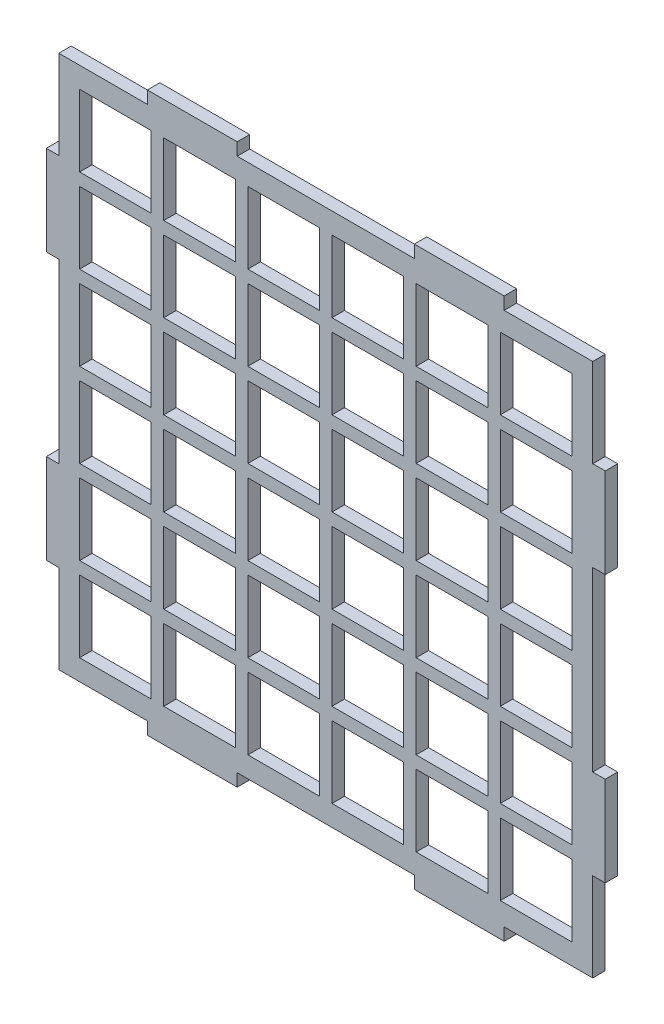
SolidWorks part; units mm, degrees
ref_plane "Front Plane" through (0, 0, 0) normal (0, 0, 1) x (1, 0, 0)
ref_plane "Top Plane" through (0, 0, 0) normal (0, 1, 0) x (1, 0, 0)
ref_plane "Right Plane" through (0, 0, 0) normal (1, 0, 0) x (0, 0, -1)
sketch "Sketch1" plane through (0, 0, 0) normal (0, 0, 1) x (1, 0, 0)
  line L0 (-64.15, -64.15) -> (64.15, 64.15) construction
  line L1 (42.5667, -64.15) -> (42.8667, -64.15)
  line L2 (21.2833, -64.15) -> (42.5667, -64.15) construction
  line L3 (0, -64.15) -> (-21.2833, -64.15)
  line L4 (21.2833, -64.15) -> (0, -64.15)
  line L5 (-42.8667, -64.15) -> (-64.15, -64.15)
  line L6 (64.15, 0) -> (64.15, 21.2833)
  line L7 (64.15, -21.2833) -> (64.15, 0)
  line L8 (64.15, -42.8667) -> (64.15, -64.15)
  line L9 (64.15, -64.15) -> (42.8667, -64.15)
  line L10 (64.15, 64.15) -> (64.15, 42.8667)
  line L11 (-21.2833, -64.15) -> (-21.2833, -67.15)
  line L12 (-42.8667, -67.15) -> (-42.8667, -64.15)
  line L13 (-21.2833, -67.15) -> (-42.8667, -67.15)
  line L14 (42.8667, -64.15) -> (42.8667, -67.15)
  line L15 (21.2833, -67.15) -> (21.2833, -64.15)
  line L16 (42.8667, -67.15) -> (21.2833, -67.15)
  line L17 (64.15, -21.2833) -> (67.15, -21.2833)
  line L18 (42.8667, 67.15) -> (21.2833, 67.15)
  line L19 (21.2833, 67.15) -> (21.2833, 64.15)
  line L21 (42.8667, 64.15) -> (42.8667, 67.15)
  line L22 (-21.2833, 67.15) -> (-42.8667, 67.15)
  line L23 (-42.8667, 67.15) -> (-42.8667, 64.15)
  line L25 (-21.2833, 64.15) -> (-21.2833, 67.15)
  line L26 (-67.15, 42.8667) -> (-67.15, 21.2833)
  line L27 (-67.15, 21.2833) -> (-64.15, 21.2833)
  line L29 (-64.15, 42.8667) -> (-67.15, 42.8667)
  line L30 (-67.15, -21.2833) -> (-67.15, -42.8667)
  line L31 (-67.15, -42.8667) -> (-64.15, -42.8667)
  line L33 (-64.15, -21.2833) -> (-67.15, -21.2833)
  line L34 (64.15, 64.15) -> (42.8667, 64.15)
  line L35 (-64.15, 64.15) -> (-64.15, 42.8667)
  line L36 (-42.8667, 64.15) -> (-64.15, 64.15)
  line L37 (-21.2833, 64.15) -> (0, 64.15)
  line L38 (0, 64.15) -> (21.2833, 64.15)
  line L39 (-64.15, -42.8667) -> (-64.15, -64.15)
  line L40 (-64.15, 21.2833) -> (-64.15, 0)
  line L41 (-64.15, 0) -> (-64.15, -21.2833)
  line L42 (-64.15, 21.2833) -> (-64.15, 42.5667) construction
  line L43 (-64.15, 42.5667) -> (-64.15, 42.8667) construction
  line L44 (67.15, -42.8667) -> (64.15, -42.8667)
  line L45 (67.15, -21.2833) -> (67.15, -42.8667)
  line L46 (64.15, 42.8667) -> (67.15, 42.8667)
  line L47 (67.15, 21.2833) -> (64.15, 21.2833)
  line L48 (67.15, 42.8667) -> (67.15, 21.2833)
  point P7 (0, 0)
  point P10 (0, 0)
  dimension "D1" = 3
  dimension "D2" = 128.3
  dimension "D3" = 0.3
extrude "Boss-Extrude1" add sketch "Sketch1" along normal blind 3 contours L39 L0 L34 L21 L18 L19 L38 L37 L25 L22 L23 L36 L35 L43 L42 L40 L41 L33 L30 L31 | L0 L5 L12 L13 L11 L3 L4 L2 L1 L9 L8 L44 L45 L17 L7 L6 L47 L48 L46 L10
sketch "Sketch2" plane through (0, 0, 3) normal (0, 0, 1) x (1, 0, 0)
  line L0 (-64.15, 59.15) -> (-59.15, 59.15) construction
  line L1 (-64.15, 64.15) -> (-64.15, 42.8667) construction
  line L2 (-59.15, 59.15) -> (-59.15, 64.15) construction
  line L3 (-42.8667, 64.15) -> (-64.15, 64.15) construction
  line L4 (-64.15, -64.15) -> (64.15, 64.15) construction
  line L5 (-64.15, -64.15) -> (64.15, 64.15) construction
  line L6 (59.15, -64.15) -> (59.15, -59.15) construction
  line L7 (59.15, -59.15) -> (64.15, -59.15) construction
  line L8 (-59.15, 59.15) -> (-59.15, 41.9333)
  line L9 (-59.15, 59.15) -> (-41.9333, 59.15)
  line L10 (-59.15, 41.9333) -> (-41.9333, 41.9333)
  line L11 (-41.9333, 59.15) -> (-41.9333, 41.9333)
  line L12 (-38.9333, 59.15) -> (-38.9333, 41.9333)
  line L13 (-38.9333, 59.15) -> (-21.7167, 59.15)
  line L14 (-21.7167, 59.15) -> (-21.7167, 41.9333)
  line L15 (-38.9333, 41.9333) -> (-21.7167, 41.9333)
  line L16 (-18.7167, 59.15) -> (-18.7167, 41.9333)
  line L17 (-18.7167, 59.15) -> (-1.5, 59.15)
  line L18 (-1.5, 59.15) -> (-1.5, 41.9333)
  line L19 (-18.7167, 41.9333) -> (-1.5, 41.9333)
  line L20 (1.5, 59.15) -> (1.5, 41.9333)
  line L21 (1.5, 59.15) -> (18.7167, 59.15)
  line L22 (18.7167, 59.15) -> (18.7167, 41.9333)
  line L23 (1.5, 41.9333) -> (18.7167, 41.9333)
  line L24 (21.7167, 59.15) -> (21.7167, 41.9333)
  line L25 (21.7167, 59.15) -> (38.9333, 59.15)
  line L26 (38.9333, 59.15) -> (38.9333, 41.9333)
  line L27 (21.7167, 41.9333) -> (38.9333, 41.9333)
  line L28 (41.9333, 59.15) -> (41.9333, 41.9333)
  line L29 (41.9333, 59.15) -> (59.15, 59.15)
  line L30 (59.15, 59.15) -> (59.15, 41.9333)
  line L31 (41.9333, 41.9333) -> (59.15, 41.9333)
  line L32 (-38.9333, 38.9333) -> (-38.9333, 21.7167)
  line L33 (-38.9333, 38.9333) -> (-21.7167, 38.9333)
  line L34 (-21.7167, 38.9333) -> (-21.7167, 21.7167)
  line L35 (-38.9333, 21.7167) -> (-21.7167, 21.7167)
  line L36 (-18.7167, 38.9333) -> (-18.7167, 21.7167)
  line L37 (-18.7167, 38.9333) -> (-1.5, 38.9333)
  line L38 (-1.5, 38.9333) -> (-1.5, 21.7167)
  line L39 (-18.7167, 21.7167) -> (-1.5, 21.7167)
  line L40 (1.5, 38.9333) -> (1.5, 21.7167)
  line L41 (1.5, 38.9333) -> (18.7167, 38.9333)
  line L42 (18.7167, 38.9333) -> (18.7167, 21.7167)
  line L43 (1.5, 21.7167) -> (18.7167, 21.7167)
  line L44 (21.7167, 38.9333) -> (21.7167, 21.7167)
  line L45 (21.7167, 38.9333) -> (38.9333, 38.9333)
  line L46 (38.9333, 38.9333) -> (38.9333, 21.7167)
  line L47 (21.7167, 21.7167) -> (38.9333, 21.7167)
  line L48 (41.9333, 38.9333) -> (41.9333, 21.7167)
  line L49 (41.9333, 38.9333) -> (59.15, 38.9333)
  line L50 (59.15, 38.9333) -> (59.15, 21.7167)
  line L51 (41.9333, 21.7167) -> (59.15, 21.7167)
  line L52 (-38.9333, 18.7167) -> (-38.9333, 1.5)
  line L53 (-38.9333, 18.7167) -> (-21.7167, 18.7167)
  line L54 (-21.7167, 18.7167) -> (-21.7167, 1.5)
  line L55 (-38.9333, 1.5) -> (-21.7167, 1.5)
  line L56 (-18.7167, 18.7167) -> (-18.7167, 1.5)
  line L57 (-18.7167, 18.7167) -> (-1.5, 18.7167)
  line L58 (-1.5, 18.7167) -> (-1.5, 1.5)
  line L59 (-18.7167, 1.5) -> (-1.5, 1.5)
  line L60 (1.5, 18.7167) -> (1.5, 1.5)
  line L61 (1.5, 18.7167) -> (18.7167, 18.7167)
  line L62 (18.7167, 18.7167) -> (18.7167, 1.5)
  line L63 (1.5, 1.5) -> (18.7167, 1.5)
  line L64 (21.7167, 18.7167) -> (21.7167, 1.5)
  line L65 (21.7167, 18.7167) -> (38.9333, 18.7167)
  line L66 (38.9333, 18.7167) -> (38.9333, 1.5)
  line L67 (21.7167, 1.5) -> (38.9333, 1.5)
  line L68 (41.9333, 18.7167) -> (41.9333, 1.5)
  line L69 (41.9333, 18.7167) -> (59.15, 18.7167)
  line L70 (59.15, 18.7167) -> (59.15, 1.5)
  line L71 (41.9333, 1.5) -> (59.15, 1.5)
  line L72 (-38.9333, -1.5) -> (-38.9333, -18.7167)
  line L73 (-38.9333, -1.5) -> (-21.7167, -1.5)
  line L74 (-21.7167, -1.5) -> (-21.7167, -18.7167)
  line L75 (-38.9333, -18.7167) -> (-21.7167, -18.7167)
  line L76 (-18.7167, -1.5) -> (-18.7167, -18.7167)
  line L77 (-18.7167, -1.5) -> (-1.5, -1.5)
  line L78 (-1.5, -1.5) -> (-1.5, -18.7167)
  line L79 (-18.7167, -18.7167) -> (-1.5, -18.7167)
  line L80 (1.5, -1.5) -> (1.5, -18.7167)
  line L81 (1.5, -1.5) -> (18.7167, -1.5)
  line L82 (18.7167, -1.5) -> (18.7167, -18.7167)
  line L83 (1.5, -18.7167) -> (18.7167, -18.7167)
  line L84 (21.7167, -1.5) -> (21.7167, -18.7167)
  line L85 (21.7167, -1.5) -> (38.9333, -1.5)
  line L86 (38.9333, -1.5) -> (38.9333, -18.7167)
  line L87 (21.7167, -18.7167) -> (38.9333, -18.7167)
  line L88 (41.9333, -1.5) -> (41.9333, -18.7167)
  line L89 (41.9333, -1.5) -> (59.15, -1.5)
  line L90 (59.15, -1.5) -> (59.15, -18.7167)
  line L91 (41.9333, -18.7167) -> (59.15, -18.7167)
  line L92 (-38.9333, -21.7167) -> (-38.9333, -38.9333)
  line L93 (-38.9333, -21.7167) -> (-21.7167, -21.7167)
  line L94 (-21.7167, -21.7167) -> (-21.7167, -38.9333)
  line L95 (-38.9333, -38.9333) -> (-21.7167, -38.9333)
  line L96 (-18.7167, -21.7167) -> (-18.7167, -38.9333)
  line L97 (-18.7167, -21.7167) -> (-1.5, -21.7167)
  line L98 (-1.5, -21.7167) -> (-1.5, -38.9333)
  line L99 (-18.7167, -38.9333) -> (-1.5, -38.9333)
  line L100 (1.5, -21.7167) -> (1.5, -38.9333)
  line L101 (1.5, -21.7167) -> (18.7167, -21.7167)
  line L102 (18.7167, -21.7167) -> (18.7167, -38.9333)
  line L103 (1.5, -38.9333) -> (18.7167, -38.9333)
  line L104 (21.7167, -21.7167) -> (21.7167, -38.9333)
  line L105 (21.7167, -21.7167) -> (38.9333, -21.7167)
  line L106 (38.9333, -21.7167) -> (38.9333, -38.9333)
  line L107 (21.7167, -38.9333) -> (38.9333, -38.9333)
  line L108 (41.9333, -21.7167) -> (41.9333, -38.9333)
  line L109 (41.9333, -21.7167) -> (59.15, -21.7167)
  line L110 (59.15, -21.7167) -> (59.15, -38.9333)
  line L111 (41.9333, -38.9333) -> (59.15, -38.9333)
  line L112 (-38.9333, -41.9333) -> (-38.9333, -59.15)
  line L113 (-38.9333, -41.9333) -> (-21.7167, -41.9333)
  line L114 (-21.7167, -41.9333) -> (-21.7167, -59.15)
  line L115 (-38.9333, -59.15) -> (-21.7167, -59.15)
  line L116 (-18.7167, -41.9333) -> (-18.7167, -59.15)
  line L117 (-18.7167, -41.9333) -> (-1.5, -41.9333)
  line L118 (-1.5, -41.9333) -> (-1.5, -59.15)
  line L119 (-18.7167, -59.15) -> (-1.5, -59.15)
  line L120 (1.5, -41.9333) -> (1.5, -59.15)
  line L121 (1.5, -41.9333) -> (18.7167, -41.9333)
  line L122 (18.7167, -41.9333) -> (18.7167, -59.15)
  line L123 (1.5, -59.15) -> (18.7167, -59.15)
  line L124 (21.7167, -41.9333) -> (21.7167, -59.15)
  line L125 (21.7167, -41.9333) -> (38.9333, -41.9333)
  line L126 (38.9333, -41.9333) -> (38.9333, -59.15)
  line L127 (21.7167, -59.15) -> (38.9333, -59.15)
  line L128 (41.9333, -41.9333) -> (41.9333, -59.15)
  line L129 (41.9333, -41.9333) -> (59.15, -41.9333)
  line L130 (59.15, -41.9333) -> (59.15, -59.15)
  line L131 (41.9333, -59.15) -> (59.15, -59.15)
  line L132 (-59.15, 38.9333) -> (-59.15, 21.7167)
  line L133 (-59.15, 38.9333) -> (-41.9333, 38.9333)
  line L134 (-41.9333, 38.9333) -> (-41.9333, 21.7167)
  line L135 (-59.15, 21.7167) -> (-41.9333, 21.7167)
  line L136 (-59.15, 18.7167) -> (-59.15, 1.5)
  line L137 (-59.15, 18.7167) -> (-41.9333, 18.7167)
  line L138 (-41.9333, 18.7167) -> (-41.9333, 1.5)
  line L139 (-59.15, 1.5) -> (-41.9333, 1.5)
  line L140 (-59.15, -1.5) -> (-59.15, -18.7167)
  line L141 (-59.15, -1.5) -> (-41.9333, -1.5)
  line L142 (-41.9333, -1.5) -> (-41.9333, -18.7167)
  line L143 (-59.15, -18.7167) -> (-41.9333, -18.7167)
  line L144 (-59.15, -21.7167) -> (-59.15, -38.9333)
  line L145 (-59.15, -21.7167) -> (-41.9333, -21.7167)
  line L146 (-41.9333, -21.7167) -> (-41.9333, -38.9333)
  line L147 (-59.15, -38.9333) -> (-41.9333, -38.9333)
  line L148 (-59.15, -41.9333) -> (-59.15, -59.15)
  line L149 (-59.15, -41.9333) -> (-41.9333, -41.9333)
  line L150 (-41.9333, -41.9333) -> (-41.9333, -59.15)
  line L151 (-59.15, -59.15) -> (-41.9333, -59.15)
  line L152 (-59.15, 38.9333) -> (-59.15, 41.9333) construction
  line L153 (-41.9333, 59.15) -> (-38.9333, 59.15) construction
  dimension "D3" = 3
  dimension "D4" = 5
  dimension "D1" = 6
  dimension "D2" = 6
extrude "Cut-Extrude1" cut sketch "Sketch2" against normal through all
